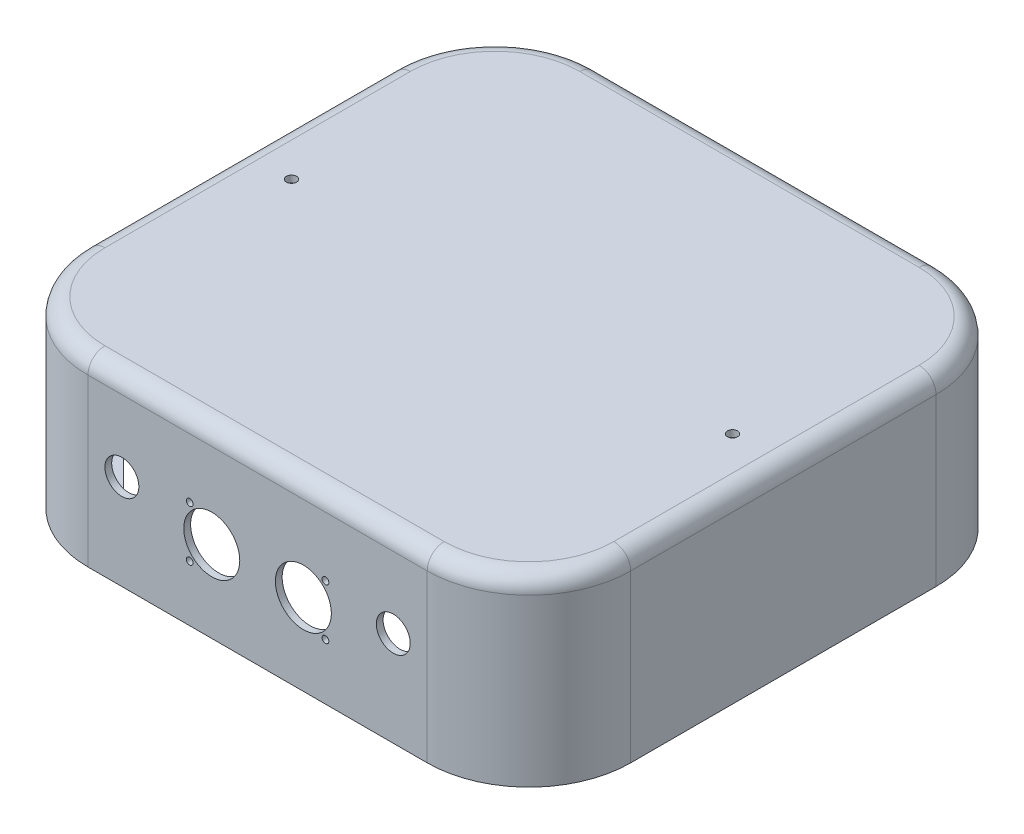
SolidWorks part; units mm, degrees
ref_plane "Front Plane" through (0, 0, 0) normal (0, 0, 1) x (1, 0, 0)
ref_plane "Top Plane" through (0, 0, 0) normal (0, 1, 0) x (1, 0, 0)
ref_plane "Right Plane" through (0, 0, 0) normal (1, 0, 0) x (0, 0, -1)
sketch "Sketch1" plane through (0, 0, 0) normal (0, 1, 0) x (1, 0, 0)
  line L0 (0, 0) -> (0, 61.2804) construction
  line L1 (-50, -75) -> (50, -75)
  line L2 (-80, -45) -> (-80, 45)
  line L3 (-50, 75) -> (50, 75)
  line L4 (80, -45) -> (80, 45)
  line L5 (-80, -75) -> (80, 75) construction
  line L6 (-80, 75) -> (80, -75) construction
  line L7 (0, 0) -> (57.2836, 0) construction
  line L8 (-80, 34.5132) -> (-39.5132, 75)
  line L9 (-80, 34.5132) -> (80, 34.5132)
  line L10 (80, 34.5132) -> (39.5132, 75)
  line L11 (80, -34.5132) -> (39.5132, -75)
  line L12 (-80, -34.5132) -> (-39.5132, -75)
  arc A0 (50, -75) -> (80, -45) centre (50, -45) ccw
  arc A1 (-50, -75) -> (-80, -45) centre (-50, -45) cw
  arc A2 (50, 75) -> (80, 45) centre (50, 45) cw
  arc A3 (-80, 45) -> (-50, 75) centre (-50, 45) cw
  circle A4 centre (-63.62, 59.6438) radius 1.5
  circle A5 centre (63.62, 59.6437) radius 1.5
  circle A6 centre (63.62, -59.6437) radius 1.5
  circle A7 centre (-63.62, -59.6438) radius 1.5
  point P0 (0, 0)
  dimension "D1" = 30
  dimension "D3" = 3
  dimension "D2" = 16.38
  dimension "D4" = 160
  dimension "D5" = 150
  dimension "D6" = 45
  dimension "D7" = 57.257
extrude "Bottom " add sketch "Sketch1" along normal blind 2 contours A1 L1 L12 L2 A7 | A3 L2 L8 L3 A4 | A2 L3 L10 L4 A5 | L1 A0 L4 L11 A6
sketch "Sketch2" plane through (0, 2, 0) normal (0, 1, 0) x (1, 0, 0)
  line L1 (50, 75) -> (-50, 75)
  line L2 (80, 45) -> (80, -45)
  line L3 (50, -75) -> (-50, -75)
  line L4 (-80, 45) -> (-80, -45)
  line L5 (80, 75) -> (-80, -75) construction
  line L6 (80, -75) -> (-80, 75) construction
  line L7 (-48, -73) -> (48, -73)
  line L8 (-78, -43) -> (-78, 43)
  line L9 (-48, 73) -> (48, 73)
  line L10 (78, -43) -> (78, 43)
  line L11 (-78, -73) -> (78, 73) construction
  line L12 (-78, 73) -> (78, -73) construction
  line L14 (0, 0) -> (0, 86.3214) construction
  arc A0 (-48, -73) -> (-78, -43) centre (-48, -43) cw
  arc A1 (-50, -75) -> (-80, -45) centre (-50, -45) cw
  arc A2 (48, -73) -> (78, -43) centre (48, -43) ccw
  arc A3 (80, -45) -> (50, -75) centre (50, -45) cw
  arc A4 (48, 73) -> (78, 43) centre (48, 43) cw
  arc A5 (50, 75) -> (80, 45) centre (50, 45) cw
  arc A6 (-78, 43) -> (-48, 73) centre (-48, 43) cw
  arc A7 (-50, 75) -> (-80, 45) centre (-50, 45) ccw
  point P0 (0, 0)
  point P7 (0, 0)
  dimension "D5" = 30
  dimension "D1" = 160
  dimension "D2" = 150
  dimension "D3" = 156
  dimension "D4" = 146
extrude "Walls" add sketch "Sketch2" along normal blind 50
sketch "Sketch3" plane through (0, 52, 0) normal (0, 1, 0) x (1, 0, 0)
  line L1 (50, -75) -> (-50, -75)
  line L2 (80, -45) -> (80, 45)
  line L3 (50, 75) -> (-50, 75)
  line L4 (-80, -45) -> (-80, 45)
  line L5 (80, -75) -> (-80, 75) construction
  line L6 (80, 75) -> (-80, -75) construction
  arc A0 (-50, -75) -> (-80, -45) centre (-50, -45) cw
  arc A1 (50, -75) -> (80, -45) centre (50, -45) ccw
  arc A2 (80, 45) -> (50, 75) centre (50, 45) ccw
  arc A3 (-50, 75) -> (-80, 45) centre (-50, 45) ccw
  point P0 (0, 0)
  dimension "D3" = 30
  dimension "D1" = 150
  dimension "D2" = 160
extrude "Top" add sketch "Sketch3" along normal blind 2
sketch "Sketch4" plane through (0, 0, 75) normal (0, 0, 1) x (1, 0, 0)
  line L0 (0, 2) -> (0, 54) construction
  line L1 (-39.5132, 2) -> (39.5132, 2) construction
  line L2 (-50, 54) -> (50, 54) construction
  line L3 (0, 16.5) -> (-20, 16.5)
  line L4 (-22.5, 14) -> (22.5, 14)
  line L5 (-22.5, 14) -> (-22.5, 34)
  line L6 (-22.5, 34) -> (22.5, 34)
  line L7 (22.5, 14) -> (22.5, 34)
  line L8 (-22.5, 14) -> (22.5, 34) construction
  line L9 (-22.5, 34) -> (22.5, 14) construction
  line L10 (0, 24) -> (-13.5, 24)
  line L11 (0, 24) -> (0, 16.5)
  circle A2 centre (-13.5, 24) radius 8.25
  circle A3 centre (-20, 16.5) radius 1
  circle A4 centre (-20, 31.5) radius 1
  circle A5 centre (20, 16.5) radius 1
  circle A6 centre (13.5, 24) radius 8.25
  circle A7 centre (20, 31.5) radius 1
  point P6 (0, 24)
  dimension "D3" = 16.5
  dimension "D7" = 2
  dimension "D1" = 45
  dimension "D2" = 20
  dimension "D4" = 13.5
  dimension "D5" = 20
  dimension "D6" = 7.5
  dimension "D8" = 20
extrude "Cut-Extrude2" cut sketch "Sketch4" against normal blind 2
sketch "Sketch5" plane through (0, 0, 75) normal (0, 0, 1) x (1, 0, 0)
  line L0 (0, 2) -> (0, 54) construction
  line L1 (-39.5132, 2) -> (39.5132, 2) construction
  line L2 (-50, 54) -> (50, 54) construction
  line L3 (0, 28) -> (-40, 28)
  circle A0 centre (-40, 28) radius 5
  circle A1 centre (40, 28) radius 5
  dimension "D1" = 10
  dimension "D2" = 40
extrude "Cut-Extrude3" cut sketch "Sketch5" against normal blind 2
sketch "Sketch6" plane through (0, 0, -75) normal (0, 0, -1) x (-1, 0, 0)
  line L0 (-50, 54) -> (-50, 0) construction
  line L1 (-50, 54) -> (50, 54) construction
  circle A0 centre (-40, 34) radius 3
  dimension "D1" = 6
  dimension "D2" = 10
  dimension "D3" = 20
extrude "Cut-Extrude4" cut sketch "Sketch6" against normal blind 2
sketch "Sketch8" plane through (0, 54, 0) normal (0, 1, 0) x (1, 0, 0)
  line L0 (-50, -75) -> (50, -75) construction
  line L1 (0, 0) -> (0, -68.9042) construction
  circle A0 centre (-65, 0) radius 1.5
  circle A1 centre (65, 0) radius 1.5
  dimension "D1" = 3
  dimension "D2" = 65
  dimension "D3" = 75
extrude "Cut-Extrude5" cut sketch "Sketch8" against normal blind 2
sketch "Sketch9" plane through (0, 2, 0) normal (0, -1, 0) x (1, 0, 0)
  line L0 (-80, 34.5132) -> (-78, 36.5132)
  line L1 (-78, 36.5132) -> (-78, -36.5132)
  line L2 (-78, -36.5132) -> (-80, -34.5132)
  line L3 (-80, -34.5132) -> (-80, 34.5132)
  line L4 (0, 0) -> (0, 60.9604) construction
  line L5 (0, 0) -> (-44.8555, 0) construction
  line L6 (-39.5132, 75) -> (-41.5132, 73)
  line L7 (-41.5132, 73) -> (41.5132, 73)
  line L8 (-48, 73) -> (48, 73) construction
  line L9 (80, 34.5132) -> (39.5132, 75) construction
  line L10 (41.5132, 73) -> (39.7455, 74.7676)
  line L11 (39.7455, 74.7676) -> (39.5132, 75)
  line L12 (39.5132, 75) -> (-39.5132, 75)
  line L13 (78, -36.5132) -> (80, -34.5132)
  line L14 (80, 34.5132) -> (78, 36.5132)
  line L15 (78, 36.5132) -> (78, -36.5132)
  line L16 (80, -34.5132) -> (80, 34.5132)
  line L17 (39.7455, -74.7676) -> (39.5132, -75)
  line L18 (41.5132, -73) -> (39.7455, -74.7676)
  line L19 (-41.5132, -73) -> (41.5132, -73)
  line L20 (39.5132, -75) -> (-39.5132, -75)
  line L21 (-39.5132, -75) -> (-41.5132, -73)
extrude "Boss-Extrude5" add sketch "Sketch9" along normal blind 2
fillet "Fillet1" radius 5 8 edges at (-71.2132, 54, 66.2132) (-71.2132, 54, -66.2132) (71.2132, 54, -66.2132) (71.2132, 54, 66.2132) (-80, 54, 0) (0, 54, -75) (80, 54, 0) (0, 54, 75)
sketch "Sketch10" plane through (0, 0, -75) normal (0, 0, -1) x (-1, 0, 0)
  line L0 (0, 0) -> (0, 15.0775) construction
  line L1 (50, 0) -> (-50, 0) construction
  line L2 (6.5, 5) -> (-6.5, 5)
  line L3 (7.5, 6) -> (7.5, 12)
  line L4 (6.5, 13) -> (-6.5, 13)
  line L5 (-7.5, 6) -> (-7.5, 12)
  line L6 (7.5, 5) -> (-7.5, 13) construction
  line L7 (7.5, 13) -> (-7.5, 5) construction
  arc A0 (-6.5, 5) -> (-7.5, 6) centre (-6.5, 6) cw
  arc A1 (6.5, 5) -> (7.5, 6) centre (6.5, 6) ccw
  arc A2 (7.5, 12) -> (6.5, 13) centre (6.5, 12) ccw
  arc A3 (-6.5, 13) -> (-7.5, 12) centre (-6.5, 12) ccw
  point P3 (0, 9)
  dimension "D4" = 1
  dimension "D1" = 15
  dimension "D2" = 8
  dimension "D3" = 5
extrude "Cut-Extrude6" cut sketch "Sketch10" against normal blind 10
